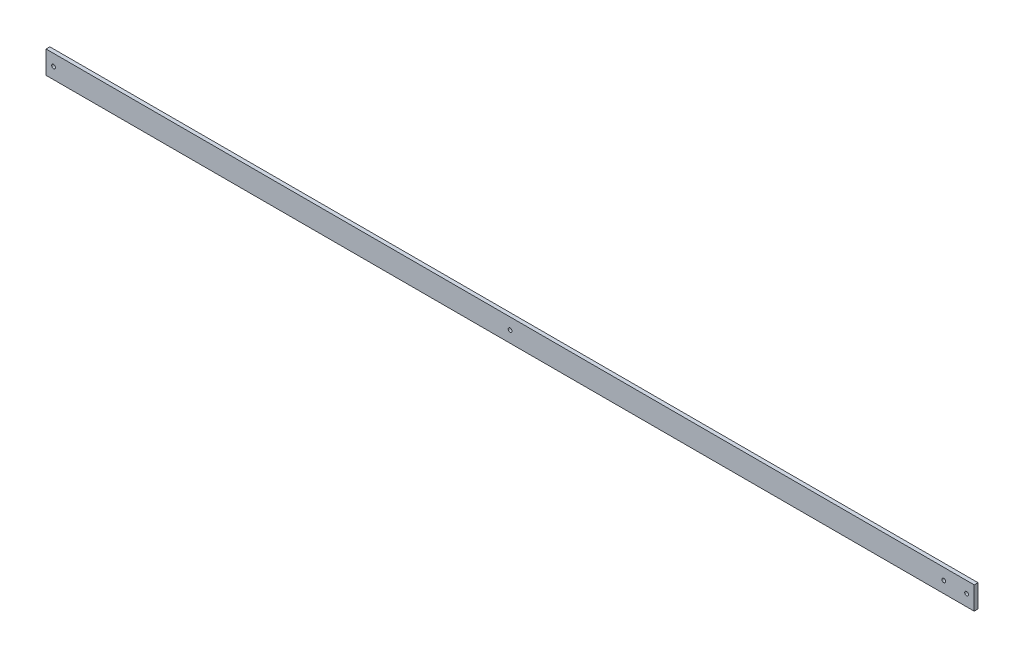
SolidWorks part; units mm, degrees
other "Markup1"
sketch "Sketch6" plane through (114.3, 38.1, 139.7) normal (0.0122, 0.8279, 0.5607) x (0.9984, -0.0412, 0.0392)
material "Balsa"
ref_plane "Front Plane" through (0, 0, 0) normal (0, 0, 1) x (1, 0, 0)
ref_plane "Top Plane" through (0, 0, 0) normal (0, 1, 0) x (1, 0, 0)
ref_plane "Right Plane" through (0, 0, 0) normal (1, 0, 0) x (0, 0, -1)
sketch "Sketch7" plane through (0, 0, 0) normal (0, 0, 1) x (1, 0, 0)
  line L1 (0, 0) -> (774.7, 0)
  line L2 (0, 0) -> (0, 19.05)
  line L3 (0, 19.05) -> (774.7, 19.05)
  line L4 (774.7, 0) -> (774.7, 19.05)
  circle A0 centre (6.35, 9.525) radius 1.5875
  circle A1 centre (387.35, 9.525) radius 1.5875
  circle A2 centre (768.35, 9.525) radius 1.5875
  circle A3 centre (749.3, 9.525) radius 1.5875
  dimension "Hole Diameter" = 3.175
  dimension "Hole Diameter2" = 3.175
  dimension "Hole Diameter3" = 3.175
  dimension "Hole Diameter4" = 3.175
  dimension "Width" = 19.05
  dimension "Total Length" = 774.7
  dimension "Hole Offset" = 6.35
  dimension "Length" = 381
  dimension "Launch Length" = 762
  dimension "Basket Mount" = 19.05
extrude "Boss-Extrude1" add sketch "Sketch7" along normal blind 3.175
equation "\"Width@Sketch7\" = \"w\""
equation "\"L1\"= 15in"
equation "\"L2\"= 12.5in"
equation "\"L3\"= 15.207in"
equation "\"L4\"= 15in"
equation "\"LL\"= 30in"
equation "\"w\"= 0.75in"
equation "\"t\"= 0.125in"
equation "\"holeD\" = 0.125in"
equation "\"holeOffset\" = 0.25in"
equation "\"Total Length@Sketch7\"=\"LL\" + 2 * \"holeOffset\""
equation "\"L\" = \"L4\""
equation "\"Hole Diameter@Sketch7\"= \"holeD\""
equation "\"Hole Offset@Sketch7\"= \"holeOffset\""
equation "\"Length@Sketch7\"= \"L\""
equation "\"Thickness@Boss-Extrude1\"= \"t\""
equation "\"Hole Diameter3@Sketch7\" = \"Hole Diameter@Sketch7\""
equation "\"Hole Diameter2@Sketch7\"= \"Hole Diameter@Sketch7\""
equation "\"Launch Length@Sketch7\"= \"LL\""
equation "\"Hole Diameter4@Sketch7\"= \"Hole Diameter@Sketch7\""
equation "\"Basket Mount@Sketch7\"= \"basketMount\""
equation "\"basketMount\" = 0.75in"
